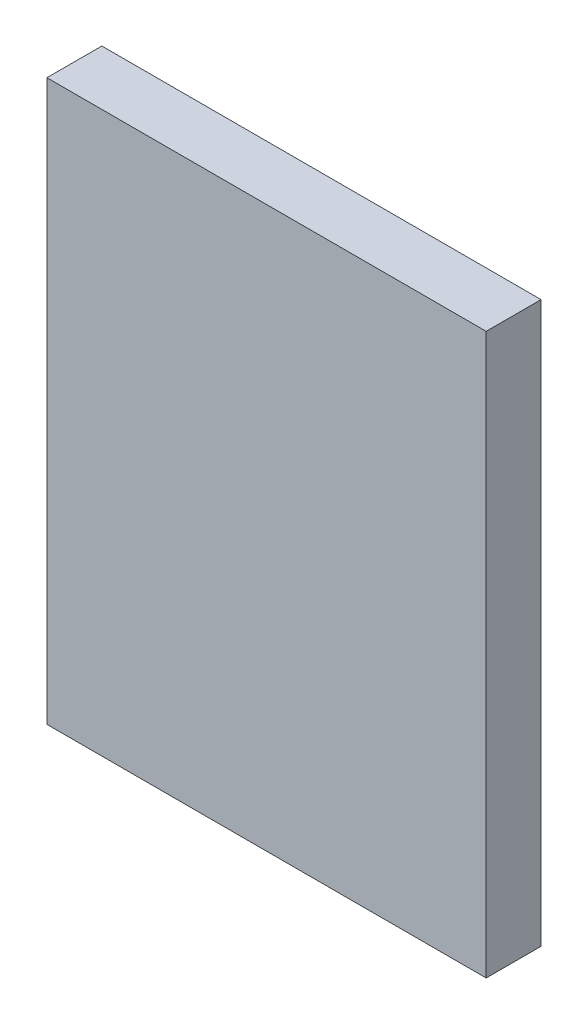
SolidWorks part; units mm, degrees
ref_plane "Płaszczyzna przednia" through (0, 0, 0) normal (0, 0, 1) x (1, 0, 0)
ref_plane "Płaszczyzna górna" through (0, 0, 0) normal (0, 1, 0) x (1, 0, 0)
ref_plane "Płaszczyzna prawa" through (0, 0, 0) normal (1, 0, 0) x (0, 0, -1)
sketch "Szkic1" plane through (0, 0, 0) normal (0, 0, 1) x (1, 0, 0)
  line L1 (-20, -25.5) -> (20, -25.5)
  line L2 (-20, -25.5) -> (-20, 25.5)
  line L3 (-20, 25.5) -> (20, 25.5)
  line L4 (20, -25.5) -> (20, 25.5)
  line L5 (-20, -25.5) -> (20, 25.5) construction
  line L6 (-20, 25.5) -> (20, -25.5) construction
  point P0 (0, 0)
  dimension "D1" = 40
  dimension "D2" = 51
extrude "Dodanie-wyciągnięcie1" add sketch "Szkic1" along normal blind 5
